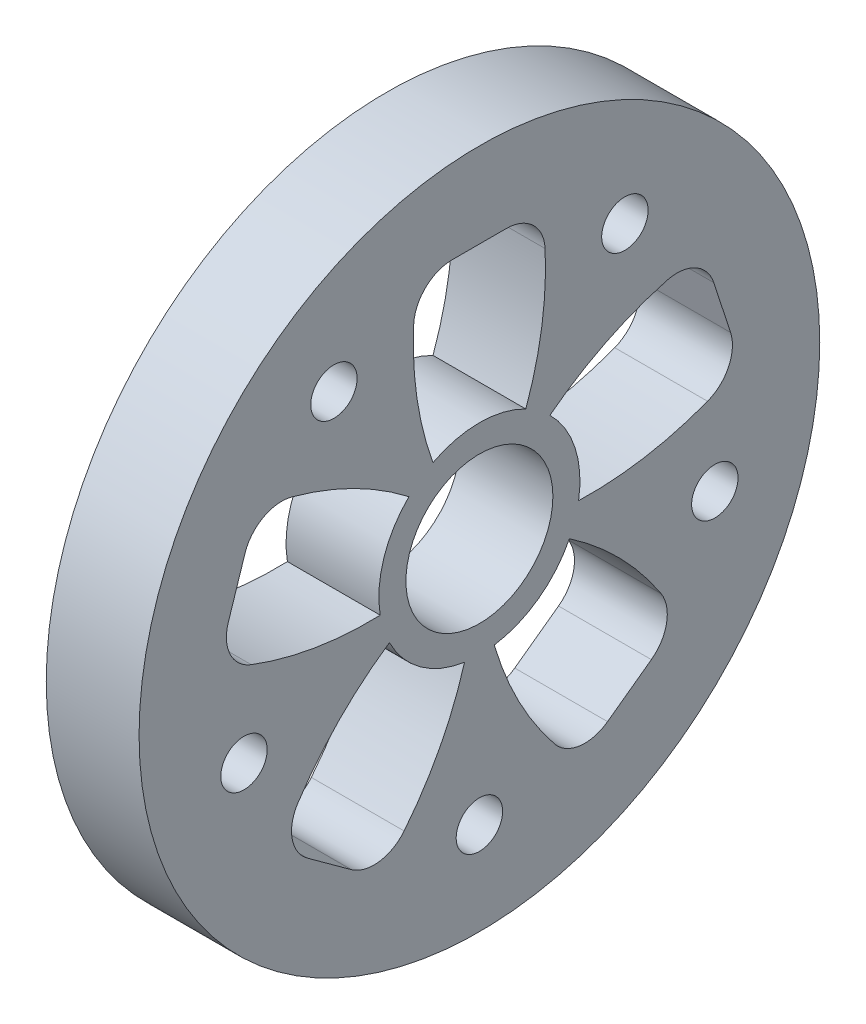
SolidWorks part; units mm, degrees
ref_plane "前视基准面" through (0, 0, 0) normal (0, 0, 1) x (1, 0, 0)
ref_plane "上视基准面" through (0, 0, 0) normal (0, 1, 0) x (1, 0, 0)
ref_plane "右视基准面" through (0, 0, 0) normal (1, 0, 0) x (0, 0, -1)
other "Configuration Table"
sketch "草图1" plane through (0, 0, 0) normal (1, 0, 0) x (0, 0, -1)
  line L0 (0, 0) -> (0, 44) construction
  line L1 (6, 0) -> (-6, 0) construction
  line L2 (-6, 0) -> (-6, 11.5326) construction
  line L3 (6, 0) -> (6, 11.5326) construction
  line L4 (-3.5, 33) -> (3.5, 33)
  line L5 (30.3033, 13.5263) -> (32.4664, 6.8689)
  line L6 (22.2285, -24.6403) -> (16.5654, -28.7548)
  line L7 (-16.5654, -28.7548) -> (-22.2285, -24.6403)
  line L8 (-32.4664, 6.8689) -> (-30.3033, 13.5263)
  circle A0 centre (0, 0) radius 44
  circle A1 centre (0, -32) radius 3
  circle A2 centre (-30.4338, -9.8885) radius 3
  circle A3 centre (-18.8091, 25.8885) radius 3
  circle A4 centre (18.8091, 25.8885) radius 3
  circle A5 centre (30.4338, -9.8885) radius 3
  circle A6 centre (0, 0) radius 9.5
  arc A8 (6, 11.5326) -> (-6, 11.5326) centre (0, 0) ccw
  arc A10 (-6, 11.5326) -> (-8.4938, 28.2485) centre (34.4531, 26.1117) cw
  arc A11 (6, 11.5326) -> (8.4938, 28.2485) centre (-34.4531, 26.1117) ccw
  arc A12 (3.5, 33) -> (8.4938, 28.2485) centre (3.5, 28) cw
  arc A13 (-3.5, 33) -> (-8.4938, 28.2485) centre (-3.5, 28) ccw
  arc A14 (12.8222, -2.1426) -> (9.114, 9.2701) centre (0, 0) ccw
  arc A15 (9.114, 9.2701) -> (24.2412, 16.8074) centre (35.4803, -24.6978) cw
  arc A16 (30.3033, 13.5263) -> (24.2412, 16.8074) centre (25.548, 11.9812) ccw
  arc A17 (32.4664, 6.8689) -> (29.4906, 0.6511) centre (27.7111, 5.3238) cw
  arc A18 (12.8222, -2.1426) -> (29.4906, 0.6511) centre (14.1871, 40.8358) ccw
  arc A19 (1.9246, -12.8568) -> (11.6328, -5.8033) centre (0, 0) ccw
  arc A20 (11.6328, -5.8033) -> (23.4757, -17.8609) centre (-12.525, -41.3758) cw
  arc A21 (22.2285, -24.6403) -> (23.4757, -17.8609) centre (19.2895, -20.5952) ccw
  arc A22 (16.5654, -28.7548) -> (9.7324, -27.846) centre (13.6264, -24.7097) cw
  arc A23 (1.9246, -12.8568) -> (9.7324, -27.846) centre (43.2212, -0.8738) ccw
  arc A24 (-11.6328, -5.8033) -> (-1.9246, -12.8568) centre (0, 0) ccw
  arc A25 (-1.9246, -12.8568) -> (-9.7324, -27.846) centre (-43.2212, -0.8738) cw
  arc A26 (-16.5654, -28.7548) -> (-9.7324, -27.846) centre (-13.6264, -24.7097) ccw
  arc A27 (-22.2285, -24.6403) -> (-23.4757, -17.8609) centre (-19.2895, -20.5952) cw
  arc A28 (-11.6328, -5.8033) -> (-23.4757, -17.8609) centre (12.525, -41.3758) ccw
  arc A29 (-9.114, 9.2701) -> (-12.8222, -2.1426) centre (0, 0) ccw
  arc A30 (-12.8222, -2.1426) -> (-29.4906, 0.6511) centre (-14.1871, 40.8358) cw
  arc A31 (-32.4664, 6.8689) -> (-29.4906, 0.6511) centre (-27.7111, 5.3238) ccw
  arc A32 (-30.3033, 13.5263) -> (-24.2412, 16.8074) centre (-25.548, 11.9812) cw
  arc A33 (-9.114, 9.2701) -> (-24.2412, 16.8074) centre (-35.4803, -24.6978) ccw
  point P6 (0, 28)
  point P16 (0, 0)
  point P71 (0, 0)
  dimension "D1" = 88
  dimension "D2" = 6
  dimension "D5" = 19
  dimension "D6" = 26
  dimension "D9" = 43
  dimension "D10" = 5
  dimension "D3" = 32
  dimension "D7" = 12
  dimension "D8" = 28
  dimension "D11" = 7
  dimension "D4" = 5
  dimension "D12" = 5
extrude "凸台-拉伸1" add sketch "草图1" along normal blind 12
